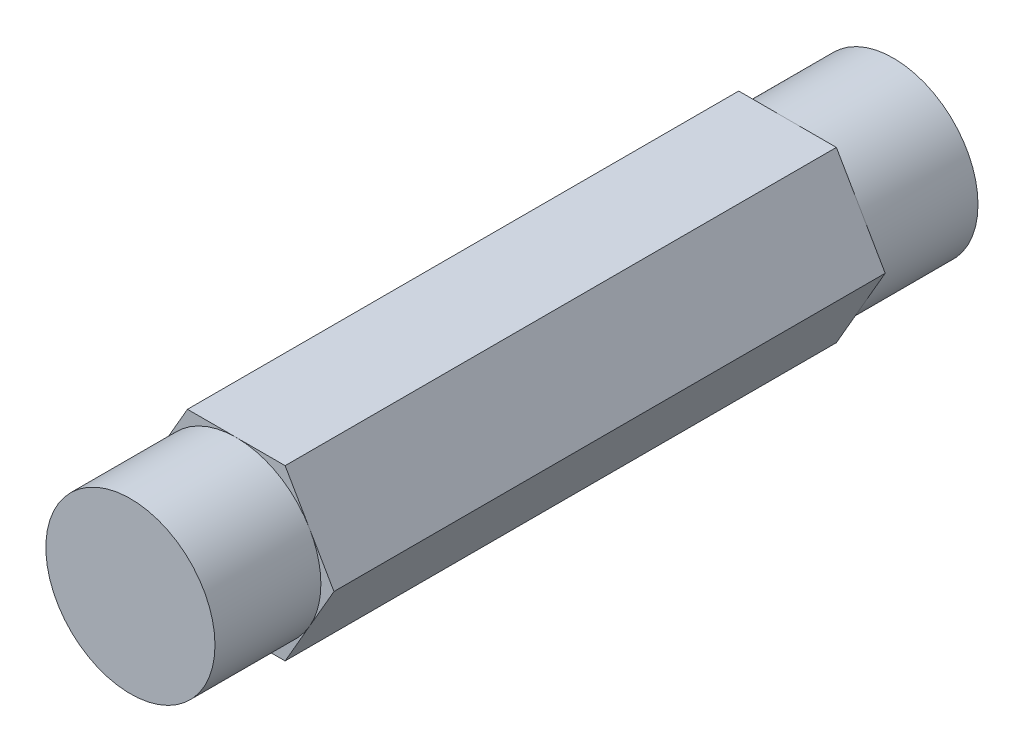
SolidWorks part; units mm, degrees
ref_plane "Front Plane" through (0, 0, 0) normal (0, 0, 1) x (1, 0, 0)
ref_plane "Top Plane" through (0, 0, 0) normal (0, 1, 0) x (1, 0, 0)
ref_plane "Right Plane" through (0, 0, 0) normal (1, 0, 0) x (0, 0, -1)
sketch "Sketch1" plane through (0, 0, 0) normal (0, 0, 1) x (1, 0, 0)
  line L1 (7.3323, 0) -> (3.6662, 6.35)
  line L2 (3.6662, 6.35) -> (-3.6662, 6.35)
  line L3 (-3.6662, 6.35) -> (-7.3323, 0)
  line L4 (-7.3323, 0) -> (-3.6662, -6.35)
  line L5 (-3.6662, -6.35) -> (3.6662, -6.35)
  line L6 (3.6662, -6.35) -> (7.3323, 0)
  circle A0 centre (0, 0) radius 6.35 construction
  dimension "D1" = 12.7
extrude "Boss-Extrude1" add sketch "Sketch1" along normal mid plane 57.2897
sketch "Sketch4" plane through (0, 0, 28.6448) normal (0, 0, 1) x (1, 0, 0)
  circle A0 centre (0, 0) radius 6.35
extrude "Cut-Extrude2" cut sketch "Sketch4" against normal blind 7.9502 flip side to cut
mirror "Mirror1" about plane through (0, 0, 0) normal (0, 0, 1) of "Cut-Extrude2"
equation "\"D1@Boss-Extrude1\"=1.625+.313+0.005+1/4+0.0625"
